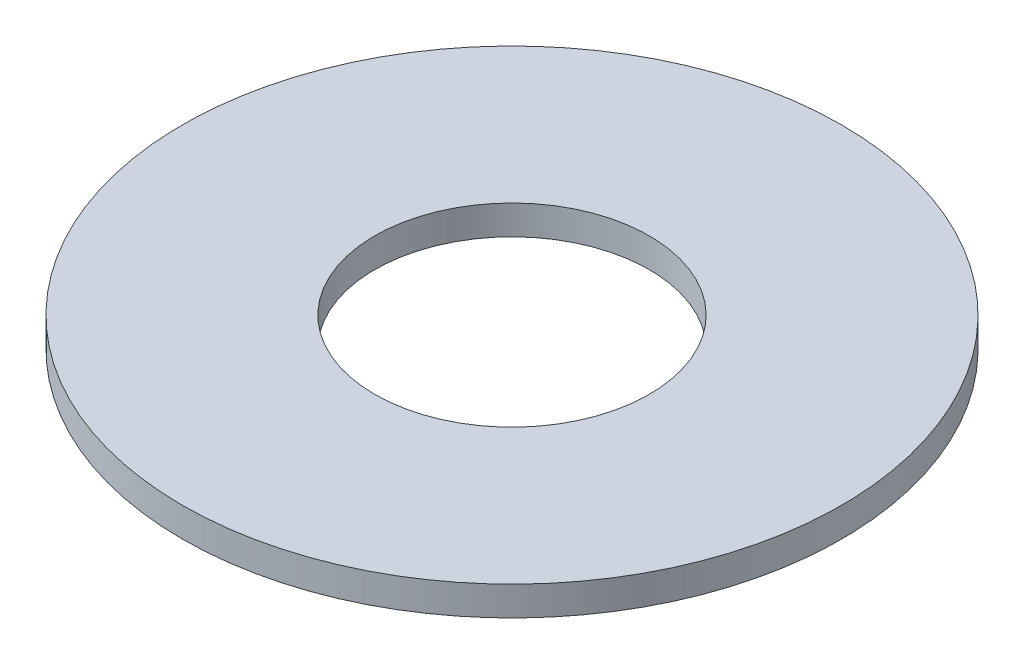
SolidWorks part; units mm, degrees
material "Brass"
ref_plane "Front Plane" through (0, 0, 0) normal (0, 0, 1) x (1, 0, 0)
ref_plane "Top Plane" through (0, 0, 0) normal (0, 1, 0) x (1, 0, 0)
ref_plane "Right Plane" through (0, 0, 0) normal (1, 0, 0) x (0, 0, -1)
sketch "Sketch1" plane through (0, 0, 0) normal (0, 1, 0) x (1, 0, 0)
  circle A0 centre (0, 0) radius 14.2875
  dimension "D1" = 28.575
extrude "Boss-Extrude1" add sketch "Sketch1" along normal blind 1.27
hole_wizard "7/16 Clearance Hole1" positions "Sketch3" profile "Sketch2" hole size "7/16" standard "ANSI Inch" end condition through all
sketch "Sketch3" plane through (0, 1.27, 0) normal (0, 1, 0) x (1, 0, 0)
  point P0 (0, 0)
sketch "Sketch2" plane through (0, 1.27, 0) normal (1, 0, 0) x (0, 0, 1)
  line L0 (0, 0) -> (0, 1.27)
  line L1 (0, 1.27) -> (5.9525, 1.27)
  line L2 (5.9525, 1.27) -> (5.9525, 0)
  line L5 (5.9525, 0) -> (0, 0)
  line L11 (0, -6.35) -> (0, 107.95) construction
  dimension "Thru Hole Dia." = 11.905
  dimension "Thru Hole Depth" = 1.27
